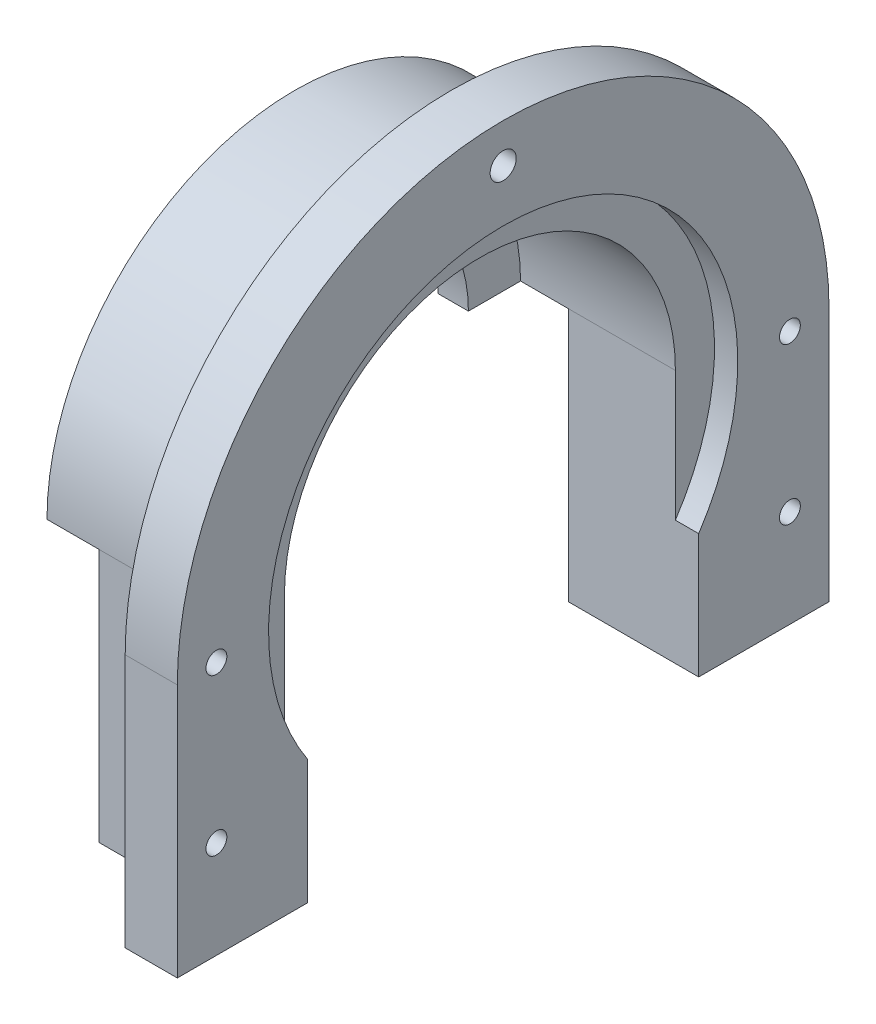
SolidWorks part; units mm, degrees
ref_plane "Front Plane" through (0, 0, 0) normal (0, 0, 1) x (1, 0, 0)
ref_plane "Top Plane" through (0, 0, 0) normal (0, 1, 0) x (1, 0, 0)
ref_plane "Right Plane" through (0, 0, 0) normal (1, 0, 0) x (0, 0, -1)
sketch "Sketch1" plane through (0, 0, 0) normal (1, 0, 0) x (0, 0, -1)
  line L7 (-47.5, 0) -> (-27.5, 0)
  line L8 (27.5, 0) -> (47.5, 0)
  line L9 (-47.5, 0) -> (-47.5, -100) construction
  line L10 (-27.5, 0) -> (-27.5, -80) construction
  line L11 (27.5, 0) -> (27.5, -80) construction
  line L12 (47.5, 0) -> (47.5, -100) construction
  line L13 (-47.5, -100) -> (47.5, -100) construction
  line L14 (-27.5, -80) -> (27.5, -80) construction
  arc A0 (27.5, 0) -> (-27.5, 0) centre (0, 0) ccw
  arc A1 (47.5, 0) -> (-47.5, 0) centre (0, 0) ccw
  dimension "D1" = 55
  dimension "D4" = 20
extrude "Boss-Extrude1" add sketch "Sketch1" along normal blind 10
sketch "Sketch2" plane through (10, 0, 0) normal (1, 0, 0) x (0, 0, -1)
  line L0 (-47.5, 0) -> (-37.5, 0)
  line L1 (37.5, 0) -> (47.5, 0)
  arc A0 (47.5, 0) -> (-47.5, 0) centre (0, 0) ccw construction
  arc A1 (47.5, 0) -> (-47.5, 0) centre (0, 0) ccw
  arc A2 (37.5, 0) -> (-37.5, 0) centre (0, 0) ccw
  dimension "D1" = 10
extrude "Boss-Extrude2" add sketch "Sketch2" along normal blind 20
ref_plane "Plane1" through (0, -58.6872, 0) normal (0, -1, 0) x (-1, 0, 0)
sketch "Sketch3" plane through (0, 0, 0) normal (0, -1, 0) x (1, 0, 0)
  line L1 (30, 47.5) -> (10, 47.5)
  line L2 (30, 47.5) -> (30, 37.5)
  line L3 (30, 37.5) -> (10, 37.5)
  line L4 (10, 47.5) -> (10, 37.5)
  line L5 (30, 37.5) -> (10, 37.5) construction
  line L7 (30, -37.5) -> (15, -37.5)
  line L8 (30, -37.5) -> (30, -47.5)
  line L9 (30, -47.5) -> (15, -47.5)
  line L10 (15, -37.5) -> (15, -47.5)
  line L11 (30, -47.5) -> (0, -47.5) construction
  line L12 (30, 37.5) -> (30, -37.5) construction
  dimension "D1" = 10
  dimension "D2" = 20
  dimension "D3" = 10
  dimension "D4" = 15
extrude "Boss-Extrude3" add sketch "Sketch3" along normal offset from surface (48.6872 mm away) 10 up to plane "Plane1"
sketch "Sketch4" plane through (30, 0, 0) normal (1, 0, 0) x (0, 0, -1)
  line L0 (62.5, -48.6872) -> (37.5, -48.6872)
  line L1 (-37.5, -48.6872) -> (-62.5, -48.6872)
  line L7 (-47.5, -48.6872) -> (-47.5, 0) construction
  line L10 (0, 47.5) -> (0, 62.5) construction
  line L11 (-62.5, 0) -> (-47.5, 0) construction
  line L12 (-62.5, 0) -> (-62.5, -63.6872)
  line L13 (-62.5, -63.6872) -> (-22.5, -63.6872)
  line L14 (-22.5, -63.6872) -> (-22.5, 0)
  line L15 (22.5, 0) -> (22.5, -63.6872)
  line L16 (22.5, -63.6872) -> (62.5, -63.6872)
  line L17 (62.5, -63.6872) -> (62.5, 0)
  line L18 (-62.5, 0) -> (-62.5, -48.6872)
  line L23 (62.5, -48.6872) -> (62.5, 0)
  line L24 (0, -125.1) -> (0, -57.1386) construction
  line L25 (37.5, -48.6872) -> (37.5, 0) construction
  line L26 (-37.5, -48.6872) -> (-37.5, 0) construction
  line L27 (37.5, -48.6872) -> (37.5, 0)
  line L28 (-37.5, -48.6872) -> (-37.5, 0)
  circle A2 centre (-55, 0) radius 2
  arc A4 (62.5, 0) -> (-62.5, 0) centre (0, 0) ccw
  arc A5 (22.5, 0) -> (-22.5, 0) centre (0, 0) ccw
  arc A6 (62.5, 0) -> (-62.5, 0) centre (0, 0) ccw
  arc A8 (47.5, 0) -> (-47.5, 0) centre (0, 0) ccw construction
  circle A9 centre (0, 55) radius 2.5
  circle A10 centre (-55, -30) radius 2
  circle A12 centre (55, -30) radius 2
  circle A13 centre (55, 0) radius 2
  arc A14 (37.5, 0) -> (-37.5, 0) centre (0, 0) ccw construction
  arc A15 (37.5, 0) -> (-37.5, 0) centre (0, 0) ccw
  dimension "D2" = 4
  dimension "D4" = 5
  dimension "D5" = 4
  dimension "D7" = 30
  dimension "D8" = 7.5
  dimension "D9" = 7.5
  dimension "D1" = 15
extrude "Boss-Extrude4" add sketch "Sketch4" along normal blind 10
sketch "Sketch7" plane through (10, 0, 0) normal (1, 0, 0) x (0, 0, -1)
  line L0 (27.5, 0) -> (37.5, 0) construction
  line L1 (27.5, 0) -> (37.5, 0)
  line L2 (-37.5, 0) -> (-27.5, 0) construction
  line L3 (-37.5, 0) -> (-27.5, 0)
  arc A0 (37.5, 0) -> (-37.5, 0) centre (0, 0) ccw construction
  arc A1 (27.5, 0) -> (-27.5, 0) centre (0, 0) ccw construction
  arc A2 (37.5, 0) -> (-37.5, 0) centre (0, 0) ccw
  arc A3 (27.5, 0) -> (-27.5, 0) centre (0, 0) ccw
extrude "Cut-Extrude1" cut sketch "Sketch7" against normal up to surface (4.1655 mm away)
ref_plane "Plane2" through (40, 0, 0) normal (-1, 0, 0) x (0, 0, 1)
sketch "Sketch8" plane through (40, 0, 0) normal (-1, 0, 0) x (0, 0, 1)
  circle A2 centre (0, 0) radius 45
  circle A3 centre (0, 0) radius 36 construction
  circle A4 centre (0, 0) radius 36
  dimension "D1" = 9
  dimension "D2" = 90
extrude "Cut-Extrude2" cut sketch "Sketch8" along normal up to surface (4.4655 mm away)
